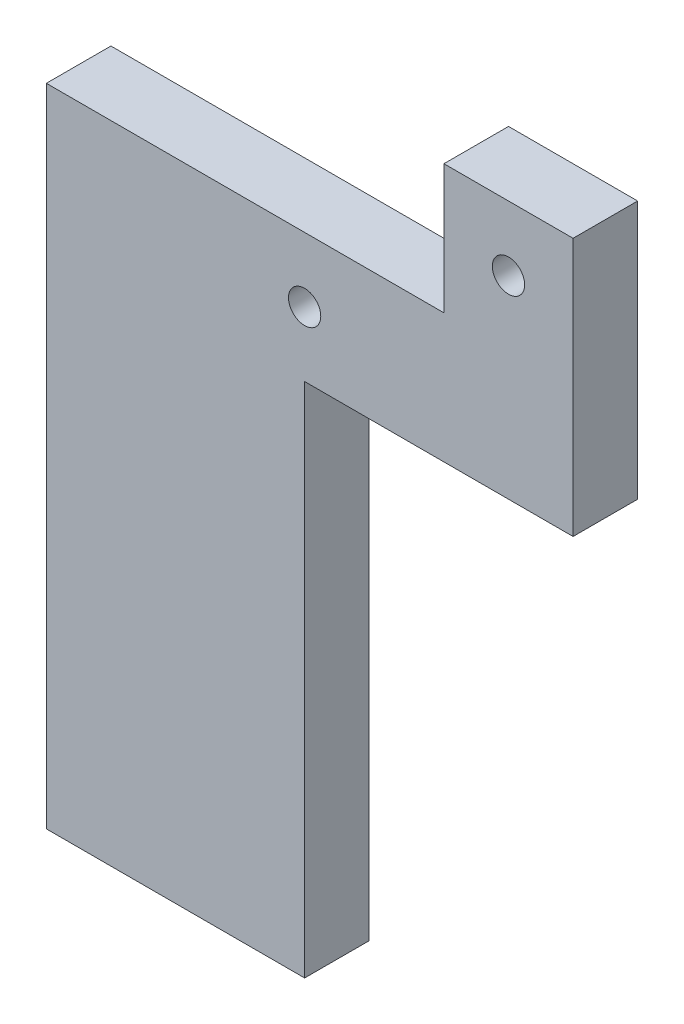
SolidWorks part; units mm, degrees
material "Balsa"
ref_plane "Front" through (0, 0, 0) normal (0, 0, 1) x (1, 0, 0)
ref_plane "Top" through (0, 0, 0) normal (0, 1, 0) x (1, 0, 0)
ref_plane "Right" through (0, 0, 0) normal (1, 0, 0) x (0, 0, -1)
sketch "Sketch1" plane through (0, 0, 0) normal (0, 0, 1) x (1, 0, 0)
  line L0 (25.4, 57.15) -> (25.4, 63.5) construction
  line L1 (25.4, 50.8) -> (51.8, 50.8)
  line L2 (0, 0) -> (0, 63.5)
  line L3 (0, 63.5) -> (39.1, 63.5)
  line L4 (51.8, 50.8) -> (51.8, 76.2)
  line L5 (25.4, 57.15) -> (25.4, 50.8) construction
  line L6 (51.8, 76.2) -> (39.1, 76.2)
  line L7 (39.1, 76.2) -> (39.1, 63.5)
  line L8 (45.45, 69.85) -> (45.45, 76.2) construction
  line L9 (30.1625, 63.5) -> (30.1625, 50.8) construction
  line L10 (30.6625, 63.5) -> (30.6625, 50.8) construction
  line L11 (40.1875, 63.5) -> (40.1875, 50.8) construction
  line L12 (40.6875, 63.5) -> (40.6875, 50.8) construction
  line L13 (25.4, 61.9125) -> (51.8, 61.9125) construction
  line L14 (45.45, 74.6125) -> (51.8, 74.6125) construction
  line L15 (25.4, 50.8) -> (25.4, 0)
  line L16 (25.4, 0) -> (0, 0)
  circle A0 centre (25.4, 57.15) radius 1.5875
  circle A1 centre (45.45, 69.85) radius 1.5875
  circle A2 centre (25.4, 57.15) radius 4.7625 construction
  circle A3 centre (35.425, 39.3076) radius 4.7625 construction
  circle A4 centre (45.45, 69.85) radius 4.7625 construction
  dimension "D1" = 3.175
  dimension "D4" = 9.525
  dimension "D2" = 12.7
  dimension "D3" = 25.4
  dimension "D6" = 0.5
  dimension "D7" = 12.7
  dimension "D8" = 12.7
  dimension "D9" = 50.8
  dimension "D5" = 0.5
extrude "Boss-Extrude2" add sketch "Sketch1" along normal blind 6.35
